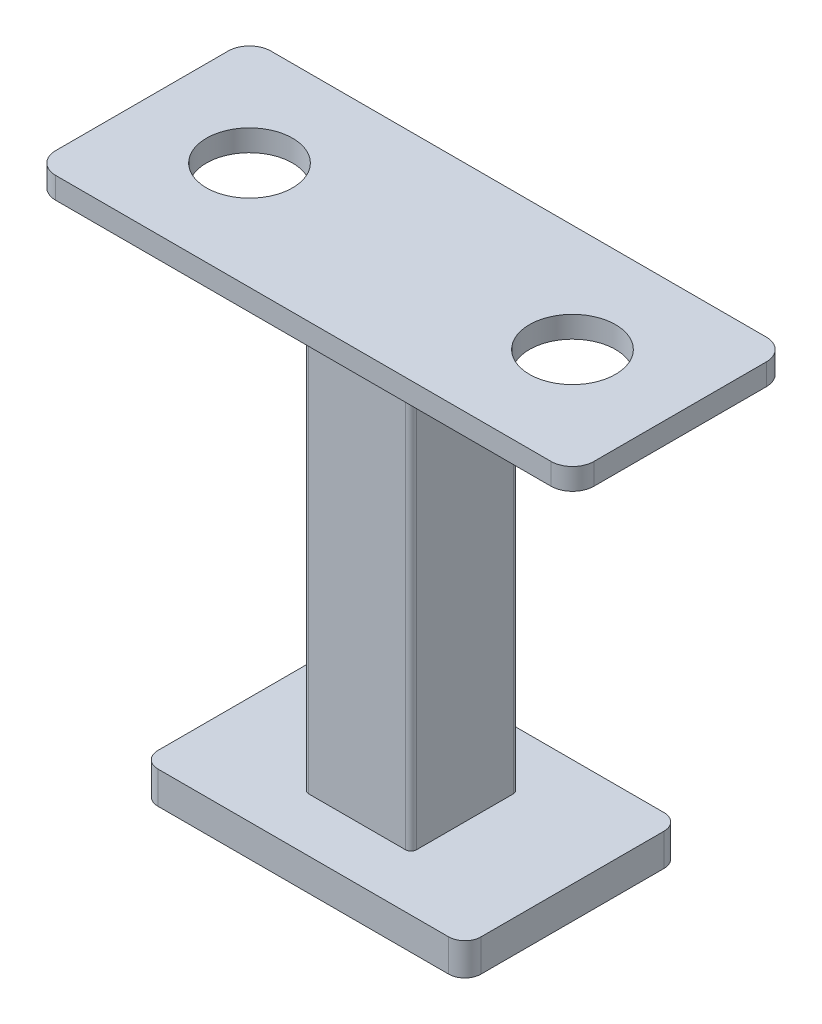
SolidWorks part; units mm, degrees
ref_plane "Front Plane" through (0, 0, 0) normal (0, 0, 1) x (1, 0, 0)
ref_plane "Top Plane" through (0, 0, 0) normal (0, 1, 0) x (1, 0, 0)
ref_plane "Right Plane" through (0, 0, 0) normal (1, 0, 0) x (0, 0, -1)
sketch "Sketch1" plane through (0, 0, 0) normal (0, 1, 0) x (1, 0, 0)
  line L0 (1.5, 0) -> (28.5, 0)
  line L1 (30, 1.5) -> (30, 18.5)
  line L2 (28.5, 20) -> (1.5, 20)
  line L3 (0, 18.5) -> (0, 1.5)
  arc A0 (30, 18.5) -> (28.5, 20) centre (28.5, 18.5) ccw
  arc A1 (30, 1.5) -> (28.5, 0) centre (28.5, 1.5) cw
  arc A2 (1.5, 0) -> (0, 1.5) centre (1.5, 1.5) cw
  arc A3 (1.5, 20) -> (0, 18.5) centre (1.5, 18.5) ccw
  point P7 (30, 20)
  point P10 (30, 0)
  point P13 (0, 0)
  dimension "D3" = 1.5
  dimension "D1" = 30
  dimension "D2" = 20
extrude "Boss-Extrude1" add sketch "Sketch1" along normal blind 3 contours L2 A3 L3 A2 L0 A1 L1 A0
sketch "Sketch3" plane through (0, 3, 0) normal (0, 1, 0) x (1, 0, 0)
  line L0 (15, 20) -> (15, 0) construction
  line L1 (28.5, 20) -> (1.5, 20) construction
  line L2 (1.5, 0) -> (28.5, 0) construction
  line L3 (0, 10) -> (30, 10) construction
  line L4 (0, 18.5) -> (0, 1.5) construction
  line L5 (30, 1.5) -> (30, 18.5) construction
  line L7 (10.5, 5) -> (19.5, 5)
  line L8 (10, 5.5) -> (10, 14.5)
  line L9 (10.5, 15) -> (19.5, 15)
  line L10 (20, 5.5) -> (20, 14.5)
  line L11 (10, 5) -> (20, 15) construction
  line L12 (10, 15) -> (20, 5) construction
  arc A0 (20, 14.5) -> (19.5, 15) centre (19.5, 14.5) ccw
  arc A1 (20, 5.5) -> (19.5, 5) centre (19.5, 5.5) cw
  arc A2 (10.5, 5) -> (10, 5.5) centre (10.5, 5.5) cw
  arc A3 (10.5, 15) -> (10, 14.5) centre (10.5, 14.5) ccw
  point P12 (15, 10)
  dimension "D3" = 0.5
  dimension "D1" = 10
  dimension "D2" = 10
extrude "Boss-Extrude2" add sketch "Sketch3" along normal blind 41
sketch "Sketch4" plane through (0, 44, 0) normal (0, 1, 0) x (1, 0, 0)
  line L0 (10.1464, 14.8536) -> (19.8536, 5.1464) construction
  line L1 (10.1464, 5.1464) -> (19.8536, 14.8536) construction
  line L3 (-8, 20) -> (38, 20)
  line L4 (-10, 18) -> (-10, 2)
  line L5 (-8, 0) -> (38, 0)
  line L6 (40, 18) -> (40, 2)
  line L7 (-10, 20) -> (40, 0) construction
  line L8 (-10, 0) -> (40, 20) construction
  arc A0 (10.5, 15) -> (10, 14.5) centre (10.5, 14.5) ccw construction
  arc A1 (19.5, 5) -> (20, 5.5) centre (19.5, 5.5) ccw construction
  arc A2 (10, 5.5) -> (10.5, 5) centre (10.5, 5.5) ccw construction
  arc A3 (20, 14.5) -> (19.5, 15) centre (19.5, 14.5) ccw construction
  arc A4 (40, 18) -> (38, 20) centre (38, 18) ccw
  arc A5 (40, 2) -> (38, 0) centre (38, 2) cw
  arc A6 (-8, 0) -> (-10, 2) centre (-8, 2) cw
  arc A7 (-8, 20) -> (-10, 18) centre (-8, 18) ccw
  point P16 (15, 10)
  point P33 (0, 0)
  dimension "D1" = 2
  dimension "D2" = 20
  dimension "D3" = 50
extrude "Boss-Extrude3" add sketch "Sketch4" along normal blind 2
sketch "Sketch5" plane through (0, 46, 0) normal (0, 1, 0) x (1, 0, 0)
  line L0 (15, 20) -> (15, 0) construction
  line L1 (38, 20) -> (-8, 20) construction
  line L2 (-8, 0) -> (38, 0) construction
  line L3 (15, 10) -> (0, 10) construction
  line L6 (15, 10) -> (30, 10) construction
  circle A0 centre (0, 10) radius 4
  circle A1 centre (30, 10) radius 4
  dimension "D2" = 8
  dimension "D3" = 8
  dimension "D1" = 15
extrude "Cut-Extrude1" cut sketch "Sketch5" against normal blind 10
